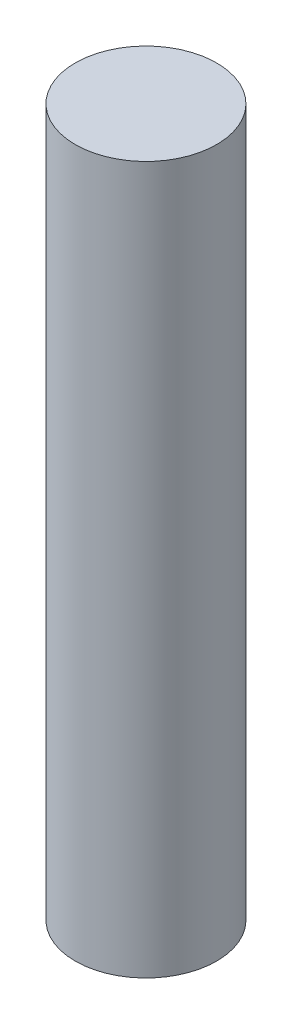
SolidWorks part; units mm, degrees
ref_plane "Front Plane" through (0, 0, 0) normal (0, 0, 1) x (1, 0, 0)
ref_plane "Top Plane" through (0, 0, 0) normal (0, 1, 0) x (1, 0, 0)
ref_plane "Right Plane" through (0, 0, 0) normal (1, 0, 0) x (0, 0, -1)
sketch "Sketch1" plane through (0, 0, 0) normal (0, 1, 0) x (1, 0, 0)
  circle A0 centre (0, 0) radius 1.5
  dimension "D1" = 3
extrude "Boss-Extrude1" add sketch "Sketch1" along normal mid plane 15
